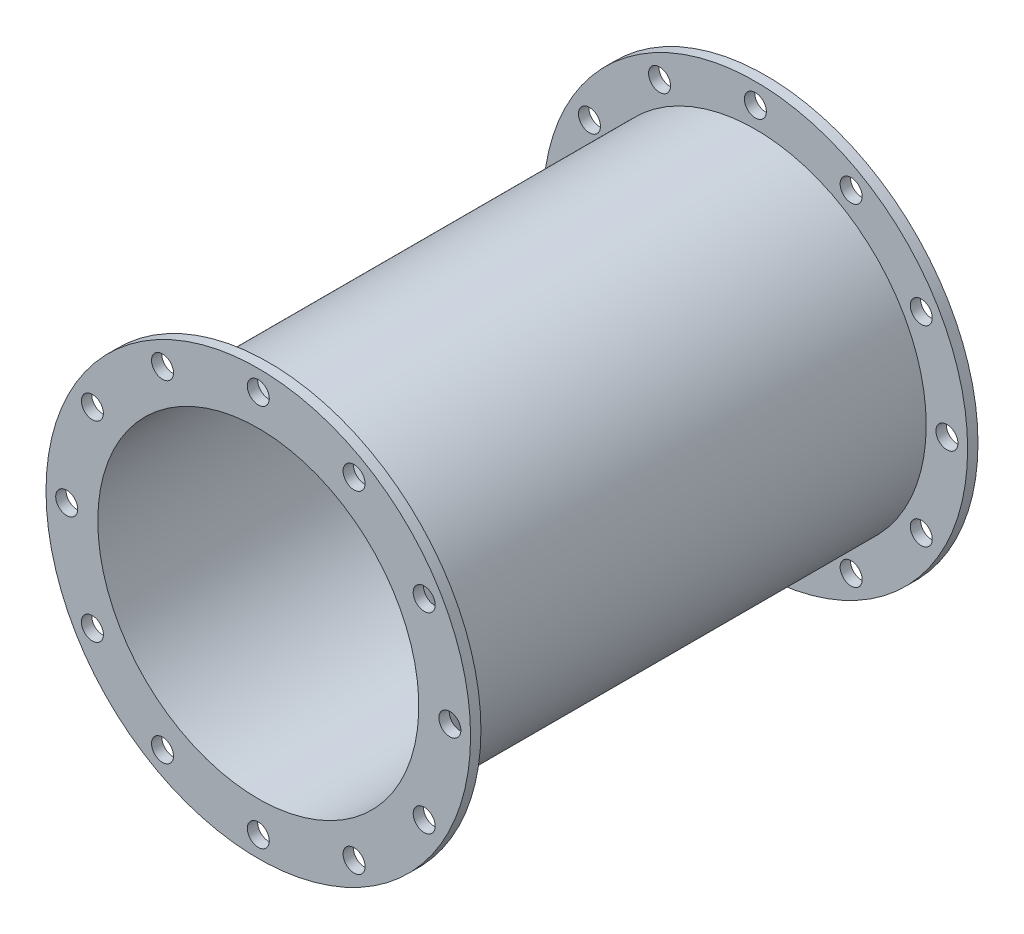
SolidWorks part; units mm, degrees
material "Acrylic (Medium-high impact)"
ref_plane "Front Plane" through (0, 0, 0) normal (0, 0, 1) x (1, 0, 0)
ref_plane "Top Plane" through (0, 0, 0) normal (0, 1, 0) x (1, 0, 0)
ref_plane "Right Plane" through (0, 0, 0) normal (1, 0, 0) x (0, 0, -1)
sketch "Sketch2" plane through (0, 0, 0) normal (0, 0, 1) x (1, 0, 0)
  circle A0 centre (0, 0) radius 104.775
  circle A1 centre (0, 0) radius 98.425
  dimension "D1" = 209.55
  dimension "D2" = 196.85
extrude "Boss-Extrude1" add sketch "Sketch2" along normal blind 304.8
sketch "Sketch3" plane through (0, 0, 0) normal (0, 0, -1) x (-1, 0, 0)
  circle A0 centre (0, 0) radius 130.175
  circle A1 centre (0, 0) radius 104.775
  dimension "D1" = 260.35
  dimension "D2" = 209.55
extrude "Boss-Extrude3" add sketch "Sketch3" against normal blind 6.35
sketch "Sketch4" plane through (0, 0, 0) normal (0, 0, -1) x (-1, 0, 0)
  line L0 (0, 0) -> (0, 130.175)
  line L1 (0, 0) -> (0, 98.425)
  circle A0 centre (0, 0) radius 130.175 construction
  circle A1 centre (0, 117.475) radius 6.35
  point P57 (0, 0)
  dimension "D2" = 12.7
  dimension "D1" = 98.425
  dimension "D3" = 12.7
hole_wizard "1/2 Clearance Hole1" positions "Sketch5" profile "Sketch7" hole size "1/2" standard "ANSI Inch" end condition through all
sketch "Sketch5" plane through (0, 0, 0) normal (0, 0, -1) x (-1, 0, 0)
  point P0 (0, 117.475)
sketch "Sketch7" plane through (0, 117.475, 0) normal (1, 0, 0) x (0, 1, 0)
  line L0 (0, 0) -> (0, 304.8)
  line L1 (0, 304.8) -> (6.7462, 304.8)
  line L2 (6.7462, 304.8) -> (6.7462, 0)
  line L5 (6.7462, 0) -> (0, 0)
  line L11 (0, -6.35) -> (0, 107.95) construction
  dimension "Thru Hole Dia." = 13.4925
  dimension "Thru Hole Depth" = 304.8
pattern_circular "CirPattern1" count 12 over 360 about axis through (0, 0, 0) along (0, 0, 1) of "1/2 Clearance Hole1"
ref_plane "Plane1" through (0, 0, 155.575) normal (0, 0, 1) x (1, 0, 0)
mirror "Mirror2" about plane through (0, 0, 155.575) normal (0, 0, 1) of "CirPattern1", "Boss-Extrude3", "Boss-Extrude1", "1/2 Clearance Hole1"
